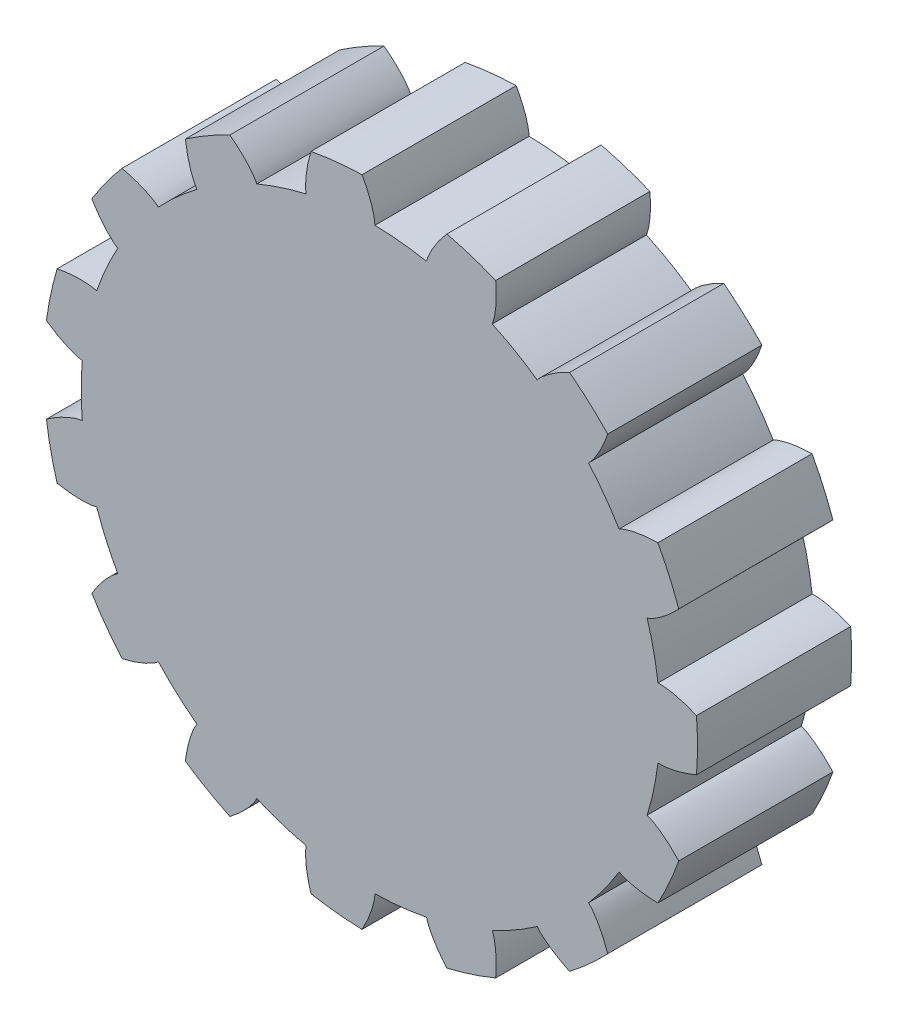
SolidWorks part; units mm, degrees
ref_plane "Front Plane" through (0, 0, 0) normal (0, 0, 1) x (1, 0, 0)
ref_plane "Top Plane" through (0, 0, 0) normal (0, 1, 0) x (1, 0, 0)
ref_plane "Right Plane" through (0, 0, 0) normal (1, 0, 0) x (0, 0, -1)
sketch "Sketch1" plane through (0, 0, 0) normal (0, 0, 1) x (1, 0, 0)
  line L0 (0, 50.8) -> (-86.2436, 50.8) construction
  line L1 (0, 50.8) -> (-94.294, 16.4798) construction
  line L2 (-16.3268, 44.8575) -> (0, 50.8) construction
  line L3 (-20.9991, 42.8696) -> (-0.8337, 52.7473) construction
  line L4 (-25.4338, 40.3966) -> (-2.1328, 55.067) construction
  line L5 (-29.5807, 37.4666) -> (-3.9826, 57.6768) construction
  line L6 (-11.4698, 46.338) -> (0.4646, 49.292) construction
  line L7 (-6.483, 47.2941) -> (0.6647, 48.2739) construction
  line L8 (-1.4229, 47.7152) -> (0.7117, 47.7788) construction
  line L9 (0.7117, 47.6833) -> (0.7117, 47.7788) construction
  line L10 (0, 0) -> (0, 88.3664) construction
  line L11 (0, 0) -> (-9.7231, 92.5095) construction
  line L12 (47.7364, 0) -> (50.8, 0) construction
  line L13 (50.8, 0) -> (53.8636, 0) construction
  circle A0 centre (0, 0) radius 50.8 construction
  circle A1 centre (0, 0) radius 47.7364 construction
  arc A2 (-16.3268, 44.8575) -> (-20.9991, 42.8696) centre (0, 0) ccw construction
  arc A3 (-20.9991, 42.8696) -> (-25.4338, 40.3966) centre (0, 0) ccw construction
  arc A4 (-25.4338, 40.3966) -> (-29.5807, 37.4666) centre (0, 0) ccw construction
  arc A5 (-16.3268, 44.8575) -> (-11.4698, 46.338) centre (0, 0) cw construction
  arc A6 (-11.4698, 46.338) -> (-6.483, 47.2941) centre (0, 0) cw construction
  arc A7 (-20.9991, 42.8696) -> (-16.3268, 44.8575) centre (0, 0) cw construction
  arc A8 (-6.483, 47.2941) -> (-1.4229, 47.7152) centre (0, 0) cw construction
  circle A9 centre (0, 0) radius 53.8636 construction
  circle A10 centre (0, 0) radius 47.6886 construction
  spline S0 degree 3 poles (0.7117, 47.6833) (0.6979, 48.228) (0.499, 49.2836) (-0.0313, 50.9803) (-1.3019, 53.9078) (-2.7759, 56.1437) (-3.9826, 57.6768) knots 0 0 0 0 0.14575 0.28684 0.476245 1 1 1 1 construction
  spline S1 degree 3 poles (-10.6101, 46.4934) (-10.7098, 47.029) (-10.7347, 48.1028) (-10.5688, 49.8728) (-9.9346, 53.0004) (-8.9577, 55.4939) (-8.0961, 57.2445) knots 0 0 0 0 0.14575 0.28684 0.476245 1 1 1 1 construction
  point P31 (0.7117, 47.7311)
  dimension "D1" = 101.6
  dimension "D4" = 5.08
  dimension "D6" = 5.08
  dimension "D12" = 5.08
  dimension "D10" = 5.08
  dimension "D17" = 107.7272
  dimension "D2" = 20
  dimension "D3" = 17.3746
  dimension "D5" = 22.4546
  dimension "D7" = 27.5346
  dimension "D8" = 5.08
  dimension "D9" = 32.6146
  dimension "D11" = 12.2946
  dimension "D13" = 7.2146
  dimension "D14" = 5.08
  dimension "D15" = 2.1346
  dimension "D16" = 6
sketch "Sketch5" plane through (0, 0, 0) normal (0, 0, 1) x (1, 0, 0)
  circle A0 centre (0, 0) radius 53.8636 construction
  circle A1 centre (0, 0) radius 47.6886 construction
  arc A2 (-1.4081, 53.8452) -> (-9.8177, 52.9613) centre (0, 0) ccw
  arc A3 (0.7117, 47.6833) -> (-10.6101, 46.4934) centre (0, 0) ccw
  spline S0 degree 3 poles (2938.0039, 595.7157) (32.4042, 4.9054) (-12.5715, 28.5044) (-10.5688, 49.8728) (2.8745, 116.1644) (300.0962, 107.3358) (-2922.936, -652.0648) knots -5.273462 -5.273462 -5.273462 -5.273462 0.14575 0.28684 0.476245 18.25188 18.25188 18.25188 18.25188 only from (-10.6101, 46.4934) to (-8.0961, 57.2445) construction
  spline S1 degree 3 poles (-2997.6577, -28.1475) (-32.716, -1.939) (6.3704, 30.4953) (-0.0313, 50.9803) (-26.9636, 113.0283) (-315.8548, 42.5968) (2994.6347, -30.1031) knots -5.273462 -5.273462 -5.273462 -5.273462 0.14575 0.28684 0.476245 18.25188 18.25188 18.25188 18.25188 only from (0.7117, 47.6833) to (-3.9826, 57.6768) construction
  spline S2 degree 3 poles (-10.6101, 46.4934) (-10.7098, 47.029) (-10.7347, 48.1028) (-10.5688, 49.8728) (-10.2412, 51.4883) (-9.9391, 52.5665) (-9.8177, 52.9613) knots 0 0 0 0 0.14575 0.28684 0.476245 0.587003 0.587003 0.587003 0.587003
  spline S3 degree 3 poles (0.7117, 47.6833) (0.6979, 48.228) (0.499, 49.2836) (-0.0313, 50.9803) (-0.6876, 52.4925) (-1.2073, 53.4842) (-1.4081, 53.8452) knots 0 0 0 0 0.14575 0.28684 0.476245 0.587003 0.587003 0.587003 0.587003
sketch "Sketch6" plane through (0, 0, 0) normal (0, 0, 1) x (1, 0, 0)
  circle A0 centre (0, 0) radius 47.6886 construction
  circle A1 centre (0, 0) radius 47.6886
extrude "Boss-Extrude3" add sketch "Sketch6" along normal blind 25.4
extrude "Boss-Extrude4" add sketch "Sketch5" along normal blind 25.4
pattern_circular "CirPattern1" count 15 over 360 about axis through (0, 0, 25.4) along (0, 0, 1) of "Boss-Extrude4"
